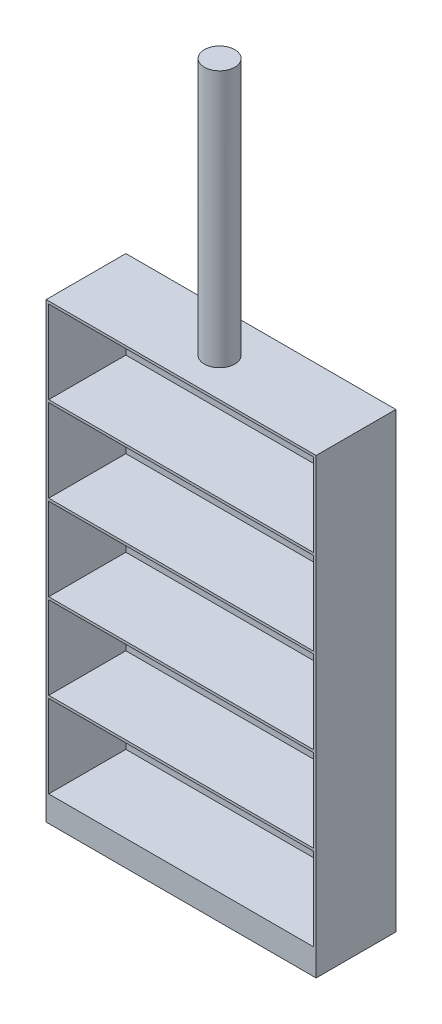
SolidWorks part; units mm, degrees
ref_plane "Alzado" through (0, 0, 0) normal (0, 0, 1) x (1, 0, 0)
ref_plane "Planta" through (0, 0, 0) normal (0, 1, 0) x (1, 0, 0)
ref_plane "Vista lateral" through (0, 0, 0) normal (1, 0, 0) x (0, 0, -1)
sketch "Croquis1" plane through (0, 0, 0) normal (0, 0, 1) x (1, 0, 0)
  line L1 (-525, -880) -> (525, -880)
  line L2 (-525, -880) -> (-525, 880)
  line L3 (-525, 880) -> (525, 880)
  line L4 (525, -880) -> (525, 880)
  line L5 (-525, -880) -> (525, 880) construction
  line L6 (-525, 880) -> (525, -880) construction
  point P0 (0, 0)
  dimension "D1" = 1050
  dimension "D2" = 1760
extrude "Saliente-Extruir1" add sketch "Croquis1" along normal blind 10
sketch "Croquis2" plane through (0, 0, 10) normal (0, 0, 1) x (1, 0, 0)
  line L0 (525, 880) -> (525, -880)
  line L1 (525, -880) -> (-525, -880)
  line L2 (-525, -880) -> (-525, 880)
  line L3 (-525, 880) -> (525, 880)
  line L4 (515, 216) -> (-515, 216)
  line L5 (515, 548) -> (-515, 548)
  line L6 (515, 548) -> (515, 870)
  line L7 (515, 870) -> (-515, 870)
  line L8 (-515, 548) -> (-515, 870)
  line L9 (515, 216) -> (515, 538)
  line L10 (515, 538) -> (-515, 538)
  line L11 (-515, 216) -> (-515, 538)
  line L12 (515, -116) -> (-515, -116)
  line L13 (515, -116) -> (515, 206)
  line L14 (515, 206) -> (-515, 206)
  line L15 (-515, -116) -> (-515, 206)
  line L16 (515, -448) -> (-515, -448)
  line L17 (515, -448) -> (515, -126)
  line L18 (515, -126) -> (-515, -126)
  line L19 (-515, -448) -> (-515, -126)
  line L20 (515, -780) -> (-515, -780)
  line L21 (515, -780) -> (515, -458)
  line L22 (515, -458) -> (-515, -458)
  line L23 (-515, -780) -> (-515, -458)
  dimension "D1" = 5
  dimension "D2" = 10
  dimension "D3" = 10
  dimension "D4" = 10
  dimension "D6" = 10
  dimension "D5" = 100
extrude "Saliente-Extruir2" add sketch "Croquis2" along normal blind 300
sketch "Croquis3" plane through (0, 880, 0) normal (0, 1, 0) x (1, 0, 0)
  circle A0 centre (0, -160.4627) radius 59.222
extrude "Saliente-Extruir3" add sketch "Croquis3" along normal blind 1000
